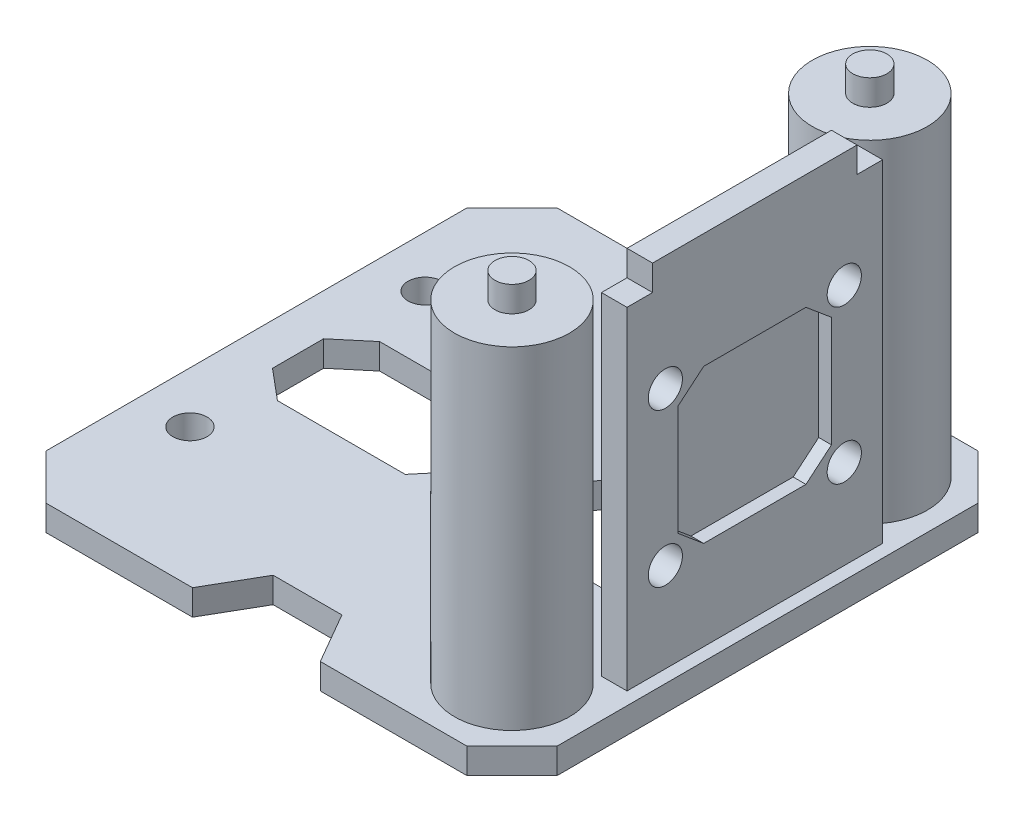
SolidWorks part; units mm, degrees
material "ABS"
ref_plane "Front Plane" through (0, 0, 0) normal (0, 0, 1) x (1, 0, 0)
ref_plane "Top Plane" through (0, 0, 0) normal (0, 1, 0) x (1, 0, 0)
ref_plane "Right Plane" through (0, 0, 0) normal (1, 0, 0) x (0, 0, -1)
sketch "Sketch1" plane through (0, 0, 0) normal (0, 1, 0) x (1, 0, 0)
  line L1 (-25.4, -25.4) -> (25.4, -25.4)
  line L2 (-25.4, -25.4) -> (-25.4, 25.4)
  line L3 (-25.4, 25.4) -> (25.4, 25.4)
  line L4 (25.4, -25.4) -> (25.4, 25.4)
  line L5 (-25.4, -25.4) -> (25.4, 25.4) construction
  line L6 (-25.4, 25.4) -> (25.4, -25.4) construction
  point P0 (0, 0)
  dimension "D1" = 50.8
extrude "Boss-Extrude1" add sketch "Sketch1" along normal blind 2.54
sketch "Sketch3" plane through (0, 2.54, 0) normal (0, 1, 0) x (1, 0, 0)
  line L0 (-25.4, 0) -> (25.4, 0) construction
  line L1 (-25.4, 25.4) -> (-25.4, -25.4) construction
  line L2 (25.4, -25.4) -> (25.4, 25.4) construction
  line L3 (0, -25.4) -> (0, 25.4) construction
  line L4 (-25.4, -25.4) -> (25.4, -25.4) construction
  line L5 (25.4, 25.4) -> (-25.4, 25.4) construction
  point P12 (-20.32, -11.684)
  point P13 (-20.32, 11.684)
  dimension "D1" = 5.08
  dimension "D2" = 11.684
  dimension "D3" = 11.684
  dimension "D4" = 5.08
hole_wizard "holes for arms" positions "Sketch7" profile "Sketch8" hole size "M3" standard "ANSI Metric" end condition through all
sketch "Sketch7" plane through (0, 2.54, 0) normal (0, 1, 0) x (1, 0, 0)
  point P0 (-20.32, -11.684)
  point P3 (-20.32, 11.684)
sketch "Sketch8" plane through (-20.32, 2.54, 11.684) normal (1, 0, 0) x (0, 0, 1)
  line L0 (0, 0) -> (0, 2.54)
  line L1 (0, 2.54) -> (1.7, 2.54)
  line L2 (1.7, 2.54) -> (1.7, 0)
  line L5 (1.7, 0) -> (0, 0)
  line L11 (0, -6.35) -> (0, 107.95) construction
  dimension "Thru Hole Dia." = 3.4
  dimension "Thru Hole Depth" = 2.54
sketch "Sketch9" plane through (0, 2.54, 0) normal (0, 1, 0) x (1, 0, 0)
  line L0 (-25.4, -25.4) -> (25.4, -25.4) construction
  line L1 (25.4, -25.4) -> (25.4, 25.4) construction
  line L2 (25.4, 0) -> (-25.4, 0) construction
  point P0 (17.78, -17.78)
  point P9 (17.78, 17.78)
  dimension "D1" = 7.62
  dimension "D2" = 7.62
hole_wizard "holes for structure" positions "Sketch10" profile "Sketch11" hole size "M3" standard "ANSI Metric" end condition through all
sketch "Sketch10" plane through (0, 2.54, 0) normal (0, 1, 0) x (1, 0, 0)
  line L0 (-25.4, 0) -> (25.4, 0) construction
  circle A0 centre (17.78, -17.78) radius 3.81
  circle A1 centre (17.78, 17.78) radius 3.81
  point P0 (17.78, -17.78)
  point P3 (17.78, 17.78)
  dimension "D1" = 7.62
sketch "Sketch11" plane through (17.78, 2.54, 17.78) normal (1, 0, 0) x (0, 0, 1)
  line L0 (0, 0) -> (0, 2.54)
  line L1 (0, 2.54) -> (1.7, 2.54)
  line L2 (1.7, 2.54) -> (1.7, 0)
  line L5 (1.7, 0) -> (0, 0)
  line L11 (0, -6.35) -> (0, 107.95) construction
  dimension "Thru Hole Dia." = 3.4
  dimension "Thru Hole Depth" = 2.54
sketch "Sketch12" plane through (0, 2.54, 0) normal (0, 1, 0) x (1, 0, 0)
  line L0 (0, -25.4) -> (0, 25.4) construction
  line L1 (-25.4, 0) -> (25.4, 0) construction
  line L2 (-20.9099, -25.4) -> (-25.4, -20.9099)
  line L3 (-25.4, -25.4) -> (25.4, -25.4) construction
  line L4 (-25.4, 25.4) -> (-25.4, -25.4) construction
  line L5 (-25.4, -25.4) -> (-25.4, -20.9099) construction
  line L6 (-25.4, -25.4) -> (-20.9099, -25.4) construction
  line L7 (-20.9099, 25.4) -> (-25.4, 20.9099)
  line L8 (20.9099, 25.4) -> (25.4, 20.9099)
  line L9 (20.9099, -25.4) -> (25.4, -20.9099)
  dimension "D1" = 45
  dimension "D2" = 45
  dimension "D3" = 6.35
extrude "corners" cut sketch "Sketch12" against normal blind 2.54 and the other way through all contours L2
ref_plane "Plane1" through (0, 0, 0) normal (-1, 0, 0) x (0, 0, 1)
ref_plane "Plane2" through (0, 0, 0) normal (0, 0, -1) x (-1, 0, 0)
mirror "mirror of corner" about plane through (0, 0, 0) normal (-1, 0, 0) of "corners"
mirror "mirror of corner 2" about plane through (0, 0, 0) normal (0, 0, -1) of "mirror of corner", "corners"
sketch "Sketch14" plane through (0, 2.54, 0) normal (0, 1, 0) x (1, 0, 0)
  line L0 (0, -25.4) -> (0, 25.4) construction
  line L1 (-25.4, 0) -> (25.4, 0) construction
  line L2 (-6.35, -25.4) -> (6.35, -25.4)
  line L3 (-20.9099, -25.4) -> (20.9099, -25.4) construction
  line L4 (-6.35, -25.4) -> (-3.4171, -20.32)
  line L5 (-3.4171, -20.32) -> (3.4171, -20.32)
  line L6 (6.35, -25.4) -> (3.4171, -20.32)
  line L7 (-6.35, 25.4) -> (-3.4171, 20.32)
  line L8 (-6.35, 25.4) -> (6.35, 25.4)
  line L9 (6.35, 25.4) -> (3.4171, 20.32)
  line L10 (-3.4171, 20.32) -> (3.4171, 20.32)
  point P14 (0, -20.32)
  dimension "D1" = 6.35
  dimension "D2" = 5.08
  dimension "D3" = 60
extrude "side cuts" cut sketch "Sketch14" against normal blind 2.54
sketch "Sketch15" plane through (0, 2.54, 0) normal (0, 1, 0) x (1, 0, 0)
  line L0 (-25.4, 0) -> (25.4, 0) construction
  line L1 (-21.2597, 2.54) -> (-21.2597, -2.54)
  line L2 (-21.2597, -2.54) -> (-18.2326, -5.08)
  line L3 (-18.2326, -5.08) -> (-5.5326, -5.08)
  line L4 (-5.5326, -5.08) -> (-1.27, 0)
  line L5 (-5.5326, 5.08) -> (-1.27, 0)
  line L6 (-21.2597, 2.54) -> (-18.2326, 5.08)
  line L7 (-18.2326, 5.08) -> (-5.5326, 5.08)
  line L8 (0, -25.4) -> (0, 25.4) construction
  point P12 (-21.2597, 0)
  dimension "D1" = 12.7
  dimension "D2" = 2.54
  dimension "D3" = 130
  dimension "D4" = 130
  dimension "D5" = 19.9897
  dimension "D6" = 5.08
  dimension "D7" = 1.27
extrude "center cut" cut sketch "Sketch15" against normal blind 2.54
mirror "mirror of center cut" about plane through (0, 0, 0) normal (-1, 0, 0) of "center cut"
sketch "Sketch16" plane through (0, 2.54, 0) normal (0, 1, 0) x (1, 0, 0)
  line L0 (1.397, 0) -> (-1.397, 0) construction
  circle A0 centre (17.78, -17.78) radius 5.715
  circle A1 centre (17.78, 17.78) radius 5.715
  circle A2 centre (17.78, -17.78) radius 1.7
  circle A3 centre (17.78, 17.78) radius 1.7
  dimension "D1" = 11.43
extrude "standoffs" add sketch "Sketch16" along normal blind 33.02
sketch "Sketch17" plane through (0, 2.54, 0) normal (0, 1, 0) x (1, 0, 0)
  line L0 (24.13, 12.7) -> (24.13, -12.7)
  line L2 (24.13, -12.7) -> (21.59, -12.7)
  line L3 (21.59, -12.7) -> (21.59, 12.7)
  line L4 (-25.4, 0) -> (25.4, 0) construction
  line L5 (1.397, 0) -> (-1.397, 0) construction
  line L6 (24.13, 12.7) -> (21.59, 12.7)
  line L7 (25.4, -20.9099) -> (25.4, 20.9099) construction
  point P13 (25.4, 0)
  point P14 (21.59, 0)
  dimension "D1" = 2.54
  dimension "D2" = 12.7
  dimension "D3" = 1.27
extrude "Boss-Extrude2" add sketch "Sketch17" along normal blind 33.02
sketch "Sketch18" plane through (0, 35.56, 0) normal (0, 1, 0) x (1, 0, 0)
  line L0 (21.59, 12.7) -> (21.59, -12.7) construction
  line L1 (21.59, -10.16) -> (24.13, -10.16)
  line L2 (21.59, -10.16) -> (21.59, -7.62)
  line L3 (21.59, -7.62) -> (24.13, -7.62)
  line L4 (24.13, -10.16) -> (24.13, -7.62)
  line L5 (24.13, -12.7) -> (24.13, 12.7) construction
  line L6 (21.59, -12.7) -> (24.13, -12.7) construction
  line L7 (-25.4, 0) -> (25.4, 0) construction
  line L8 (1.397, 0) -> (-1.397, 0) construction
  line L9 (21.59, 7.62) -> (24.13, 7.62)
  line L10 (24.13, 10.16) -> (24.13, 7.62)
  line L11 (21.59, 10.16) -> (24.13, 10.16)
  line L12 (21.59, 10.16) -> (21.59, 7.62)
  dimension "D1" = 2.54
  dimension "D2" = 7.62
  dimension "D3" = 2.54
extrude "Boss-Extrude3" add sketch "Sketch18" along normal blind 2.54
sketch "Sketch19" plane through (25.4, 0, 0) normal (1, 0, 0) x (0, 0, -1)
  line L0 (0, 35.56) -> (0, -8.328) construction
  line L1 (-7.62, 35.56) -> (7.62, 35.56) construction
  line L2 (0, -1.397) -> (0, 1.397) construction
  line L3 (-12.7, 19.05) -> (28.8292, 19.05) construction
  line L4 (-12.7, 35.56) -> (-12.7, 2.54) construction
  line L5 (-7.62, 13.5613) -> (-7.62, 24.5387)
  line L6 (-7.62, 24.5387) -> (-5.08, 26.67)
  line L7 (-5.08, 26.67) -> (5.08, 26.67)
  line L8 (7.62, 24.5387) -> (5.08, 26.67)
  line L9 (7.62, 13.5613) -> (7.62, 24.5387)
  line L10 (7.62, 13.5613) -> (5.08, 11.43)
  line L11 (-5.08, 11.43) -> (5.08, 11.43)
  line L12 (-7.62, 13.5613) -> (-5.08, 11.43)
  point P16 (0, 26.67)
  point P19 (7.62, 19.05)
  point P22 (-7.62, 19.05)
  dimension "D1" = 5.08
  dimension "D2" = 5.08
  dimension "D3" = 130
  dimension "D4" = 140
  dimension "D5" = 7.62
  dimension "D6" = 3.3157
  dimension "D7" = 7.62
extrude "Cut-Extrude1" cut sketch "Sketch19" against normal blind 2.54
sketch "Sketch20" plane through (24.13, 0, 0) normal (1, 0, 0) x (0, 0, -1)
  line L0 (-12.7, 19.05) -> (12.7, 19.05) construction
  line L1 (-12.7, 35.56) -> (-12.7, 2.54) construction
  line L2 (12.7, 35.56) -> (12.7, 2.54) construction
  line L3 (0, 35.56) -> (0, -5.9081) construction
  line L4 (-7.62, 35.56) -> (7.62, 35.56) construction
  line L5 (0, -1.397) -> (0, 1.397) construction
  point P0 (-8.89, 26.67)
  dimension "D1" = 7.62
  dimension "D2" = 8.89
hole_wizard "M3 Clearance Hole1" positions "Sketch21" profile "Sketch22" hole size "M3" standard "ANSI Metric" end condition through all
sketch "Sketch21" plane through (24.13, 0, 0) normal (1, 0, 0) x (0, 0, -1)
  point P0 (-8.89, 26.67)
sketch "Sketch22" plane through (24.13, 26.67, 8.89) normal (0, 1, 0) x (0, 0, -1)
  line L0 (0, 0) -> (0, 49.53)
  line L1 (0, 49.53) -> (1.7, 49.53)
  line L2 (1.7, 49.53) -> (1.7, 0)
  line L5 (1.7, 0) -> (0, 0)
  line L11 (0, -6.35) -> (0, 107.95) construction
  dimension "Thru Hole Dia." = 3.4
  dimension "Thru Hole Depth" = 49.53
mirror "Mirror1" about plane through (0, 0, 0) normal (0, 0, -1) of "M3 Clearance Hole1"
ref_plane "Plane4" through (0, 19.05, 0) normal (0, 1, 0) x (1, 0, 0)
mirror "Mirror2" about plane through (0, 19.05, 0) normal (0, 1, 0) of "Mirror1", "M3 Clearance Hole1"
sketch "Sketch23" plane through (0, 35.56, 0) normal (0, 1, 0) x (1, 0, 0)
  line L1 (1.397, 0) -> (-1.397, 0) construction
  circle A0 centre (17.78, -17.78) radius 1.7
  circle A1 centre (17.78, 17.78) radius 1.7
extrude "Boss-Extrude4" add sketch "Sketch23" along normal blind 2.54 separate body
sketch "Sketch24" plane through (0, 35.56, 0) normal (0, 1, 0) x (1, 0, 0)
  line L0 (24.13, -12.7) -> (24.13, 12.7) construction
  line L1 (21.59, 7.62) -> (24.13, 7.62)
  line L2 (21.59, 7.62) -> (21.59, -7.62)
  line L3 (21.59, -7.62) -> (24.13, -7.62)
  line L4 (24.13, 7.62) -> (24.13, -7.62)
  line L5 (24.13, -7.62) -> (24.13, 7.62) construction
extrude "Boss-Extrude5" add sketch "Sketch24" along normal blind 2.54
equation "\"k\"= 1.00in"
